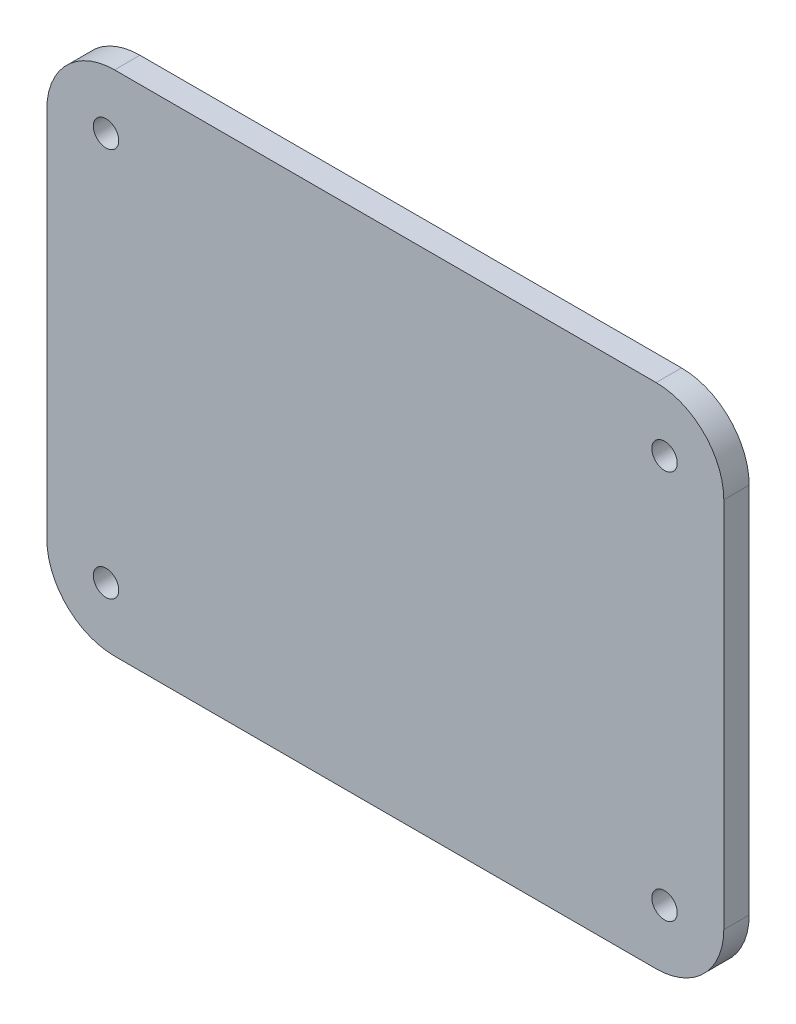
SolidWorks part; units mm, degrees
ref_plane "Front Plane" through (0, 0, 0) normal (0, 0, 1) x (1, 0, 0)
ref_plane "Top Plane" through (0, 0, 0) normal (0, 1, 0) x (1, 0, 0)
ref_plane "Right Plane" through (0, 0, 0) normal (1, 0, 0) x (0, 0, -1)
sketch "Sketch1" plane through (0, 0, 0) normal (0, 0, 1) x (1, 0, 0)
  line L1 (-40, 30) -> (40, 30)
  line L2 (-40, 30) -> (-40, -30)
  line L3 (-40, -30) -> (40, -30)
  line L4 (40, 30) -> (40, -30)
extrude "Boss-Extrude1" add sketch "Sketch1" along normal blind 3
fillet "Fillet1" radius 8 4 edges at (-40, 30, 1.5) (-40, -30, 1.5) (40, -30, 1.5) (40, 30, 1.5)
sketch "Sketch2" plane through (0, 0, 0) normal (0, 0, -1) x (-1, 0, 0)
  circle A0 centre (33, -23) radius 1.5
  circle A1 centre (33, 23) radius 1.5
  circle A2 centre (-33, 23) radius 1.5
  circle A3 centre (-33, -23) radius 1.5
extrude "Cut-Extrude1" cut sketch "Sketch2" against normal up to surface (3 mm away) up to face at (0, 0, 3)
